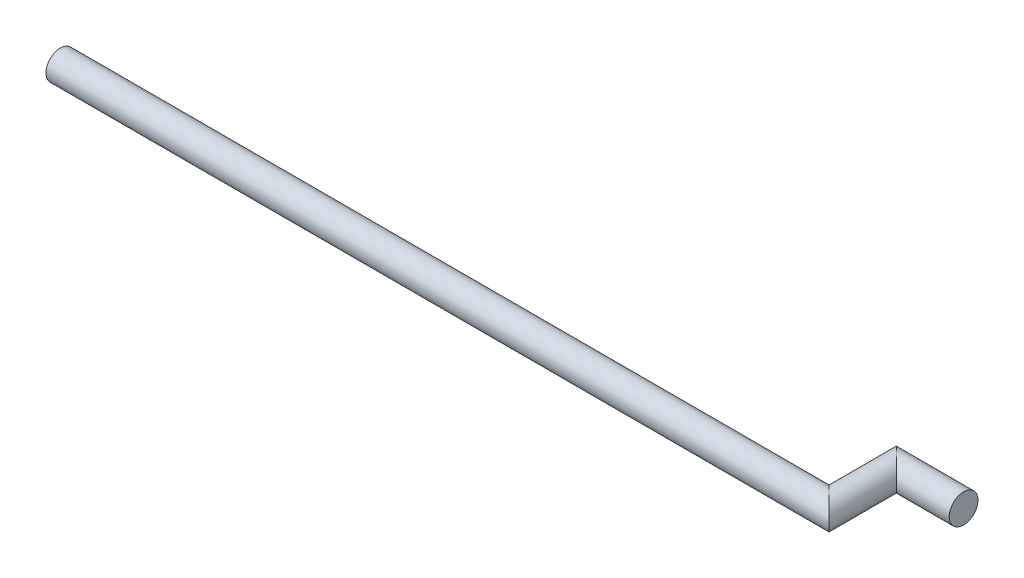
SolidWorks part; units mm, degrees
material "AISI 304"
ref_plane "Front Plane" through (0, 0, 0) normal (0, 0, 1) x (1, 0, 0)
ref_plane "Top Plane" through (0, 0, 0) normal (0, 1, 0) x (1, 0, 0)
ref_plane "Right Plane" through (0, 0, 0) normal (1, 0, 0) x (0, 0, -1)
sketch "Sketch1" plane through (0, 0, 0) normal (0, 1, 0) x (1, 0, 0)
  line L0 (0, 0) -> (40, 0)
  line L1 (40, 0) -> (40, 3.5)
  line L2 (40, 3.5) -> (43.5, 3.5)
  dimension "D1" = 40
  dimension "D2" = 3.5
  dimension "D3" = 3.5
sketch "Sketch2" plane through (0, 0, 0) normal (1, 0, 0) x (0, 0, -1)
  circle A0 centre (0, 0) radius 0.75
  dimension "D1" = 1.5
sweep "Sweep1" add profiles "Sketch2" path "Sketch1"
ref_plane "Plane1" through (0, 0, -0.75) normal (0, 0, -1) x (-1, 0, 0)
